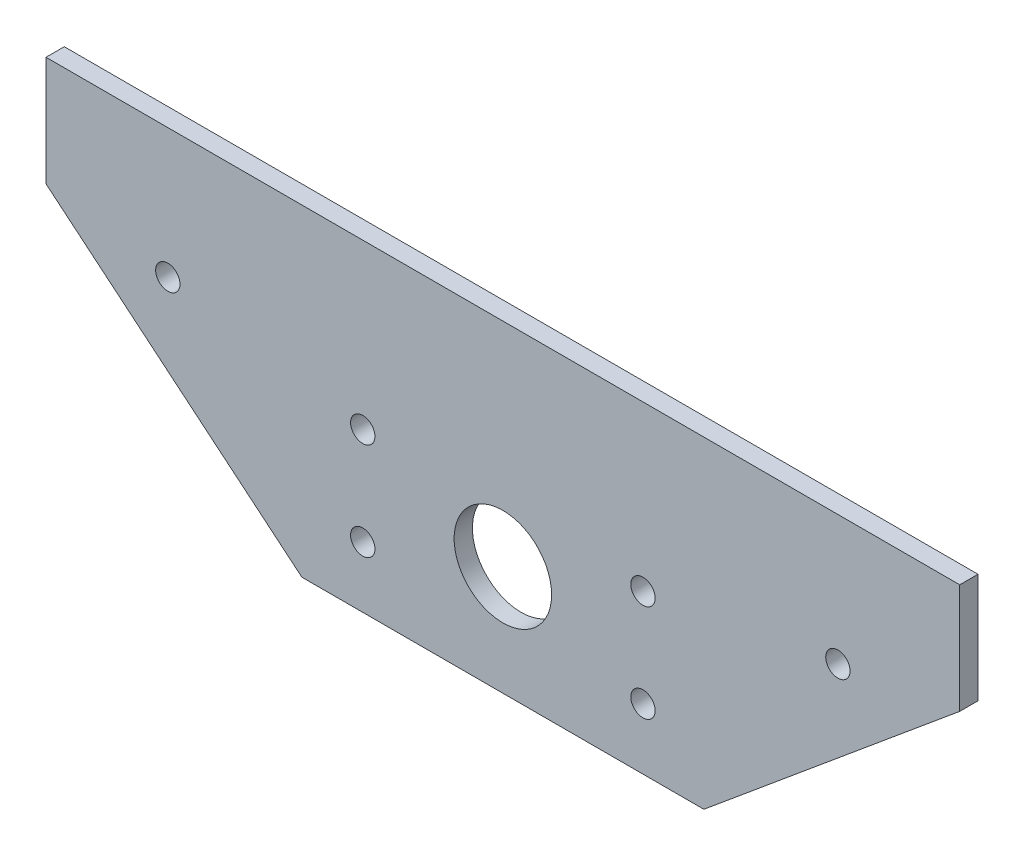
SolidWorks part; units mm, degrees
material "아크릴(내충격성)"
ref_plane "정면" through (0, 0, 0) normal (0, 0, 1) x (1, 0, 0)
ref_plane "윗면" through (0, 0, 0) normal (0, 1, 0) x (1, 0, 0)
ref_plane "우측면" through (0, 0, 0) normal (1, 0, 0) x (0, 0, -1)
sketch "스케치1" plane through (0, 0, 0) normal (0, 0, 1) x (1, 0, 0)
  line L1 (-75, 34.9192) -> (75, 34.9192)
  line L2 (-75, 34.9192) -> (-75, -35.0808)
  line L3 (-75, -35.0808) -> (75, -35.0808)
  line L4 (75, 34.9192) -> (75, -35.0808)
  line L5 (-75, 34.9192) -> (75, -35.0808) construction
  line L6 (-75, -35.0808) -> (75, 34.9192) construction
  dimension "D1" = 150
  dimension "D2" = 70
extrude "보스-돌출1" add sketch "스케치1" along normal blind 3
sketch "스케치2" plane through (0, 0, 3) normal (0, 0, 1) x (1, 0, 0)
  circle A0 centre (0, 0) radius 8
extrude "컷-돌출1" cut sketch "스케치2" against normal through all
sketch "스케치3" plane through (0, 0, 3) normal (0, 0, 1) x (1, 0, 0)
  line L0 (-56.0789, 0) -> (55.5902, 0) construction
  line L1 (0, 49.5425) -> (0, -49.6646) construction
  line L2 (-56.0789, -15) -> (55.5902, -15)
  line L3 (-56.0789, 15) -> (55.5902, 15)
  line L4 (-30, 49.5425) -> (-30, -49.6646)
  line L5 (30, 49.5425) -> (30, -49.6646)
  circle A0 centre (-23, 8) radius 2
  circle A1 centre (-23, -8) radius 2
  circle A2 centre (23, -8) radius 2
  circle A3 centre (23, 8) radius 2
  dimension "D5" = 4
  dimension "D6" = 7
  dimension "D7" = 7
  dimension "D1" = 15
  dimension "D2" = 15
  dimension "D3" = 30
  dimension "D4" = 30
extrude "컷-돌출2" cut sketch "스케치3" against normal through all contours A0 | A1 | A2 | A3
sketch "스케치4" plane through (0, 0, 3) normal (0, 0, 1) x (1, 0, 0)
  line L0 (0, 49.097) -> (0, -61.2799) construction
  line L1 (-75, 34.9192) -> (-75, -35.0808) construction
  line L2 (-75, -35.0808) -> (75, -35.0808) construction
  circle A0 centre (-55, 13.649) radius 2
  circle A1 centre (-65, -25.0808) radius 2
  circle A2 centre (65, -25.0808) radius 2
  circle A3 centre (55, 13.649) radius 2
  dimension "D1" = 4
  dimension "D2" = 4
  dimension "D3" = 10
  dimension "D4" = 10
  dimension "D5" = 20
  dimension "D6" = 40
extrude "컷-돌출3" cut sketch "스케치4" against normal through all
sketch "스케치5" plane through (0, 0, 3) normal (0, 0, 1) x (1, 0, 0)
  line L0 (-56.981, 13.9238) -> (56.981, 13.9238) construction
  line L1 (-65, -27.0808) -> (65, -27.0808) construction
  line L2 (-45, 25.7976) -> (-45, -31.7862) construction
  line L3 (-33, 24.5979) -> (-33, -29.3868) construction
  line L4 (33, 24.5979) -> (33, -29.3868) construction
  line L5 (45, 24.5979) -> (45, -30.7579) construction
  line L6 (-75, 16.9192) -> (-33, -18)
  line L16 (-75, 34.9192) -> (-75, -35.0808) construction
  line L18 (75, -35.0808) -> (75, 34.9192) construction
  line L19 (75, 16.9192) -> (75, -35.0808)
  line L20 (75, -35.0808) -> (-75, -35.0808)
  line L21 (-75, -35.0808) -> (-75, -27.0808)
  line L22 (75, 16.9192) -> (33, -18)
  line L23 (-75, 16.9192) -> (-75, -27.0808)
  line L25 (-33, -18) -> (33, -18)
  line L26 (-23, 8) -> (-23, 13.9238) construction
  line L27 (-56.981, 13.9238) -> (-23, 13.9238) construction
  circle A0 centre (-55, 13.649) radius 2 construction
  circle A1 centre (55, 13.649) radius 2 construction
  circle A2 centre (-23, -8) radius 2 construction
  circle A4 centre (65, -25.0808) radius 2 construction
  circle A5 centre (-23, 8) radius 2 construction
  circle A6 centre (23, 8) radius 2 construction
  point P9 (-65, -27.0808)
  dimension "D1" = 10
  dimension "D3" = 10
  dimension "D5" = 10
  dimension "D2" = 10
  dimension "D4" = 10
extrude "컷-돌출4" cut sketch "스케치5" against normal through all
